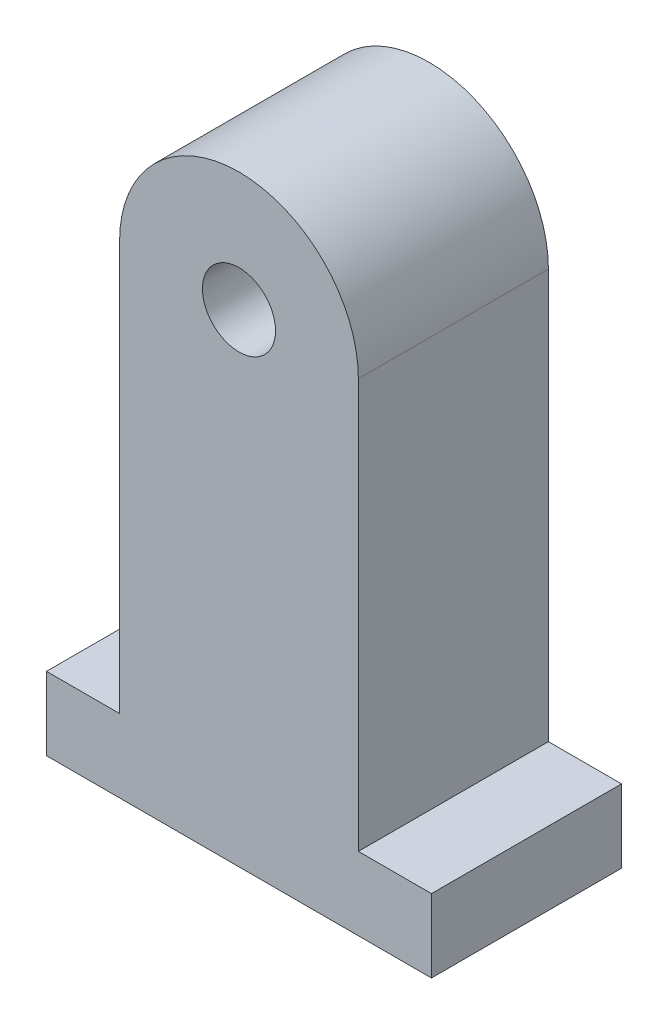
SolidWorks part; units mm, degrees
ref_plane "Front Plane" through (0, 0, 0) normal (0, 0, 1) x (1, 0, 0)
ref_plane "Top Plane" through (0, 0, 0) normal (0, 1, 0) x (1, 0, 0)
ref_plane "Right Plane" through (0, 0, 0) normal (1, 0, 0) x (0, 0, -1)
sketch "Sketch1" plane through (0, 0, 0) normal (0, 0, 1) x (1, 0, 0)
  line L0 (10.033, 0) -> (-10.033, 0)
  line L1 (-10.033, 0) -> (-10.033, 3.81)
  line L2 (-10.033, 3.81) -> (-6.223, 3.81)
  line L3 (-6.223, 3.81) -> (-6.223, 25.146)
  line L4 (0, 0) -> (0, 25.146) construction
  line L5 (10.033, 0) -> (10.033, 3.81)
  line L6 (10.033, 3.81) -> (6.223, 3.81)
  line L7 (6.223, 3.81) -> (6.223, 25.146)
  circle A0 centre (0, 25.146) radius 1.905
  arc A2 (-6.223, 25.146) -> (6.223, 25.146) centre (0, 25.146) cw
  dimension "D1" = 3.81
  dimension "D2" = 6.223
  dimension "D3" = 3.81
  dimension "D4" = 21.336
  dimension "D5" = 3.81
extrude "Boss-Extrude1" add sketch "Sketch1" along normal mid plane 9.906
